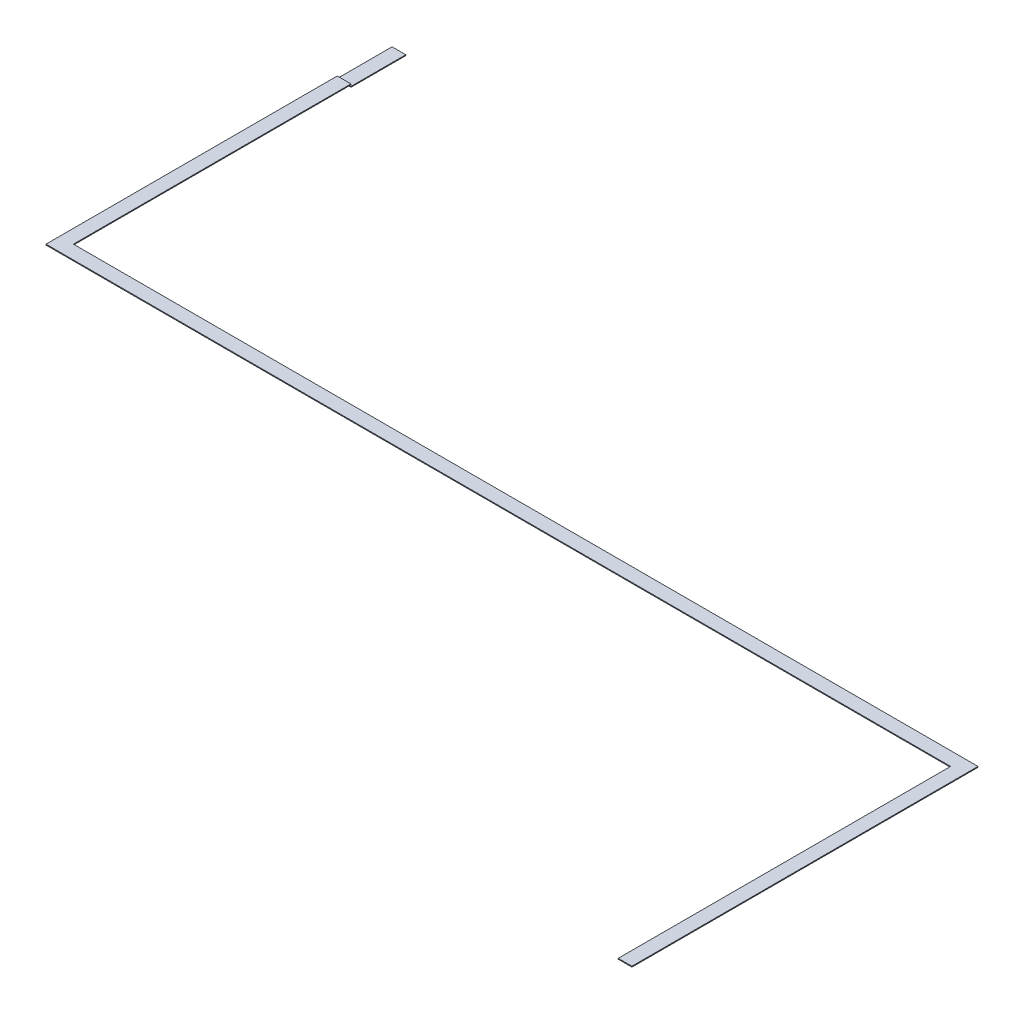
SolidWorks part; units mm, degrees
ref_plane "Front Plane" through (0, 0, 0) normal (0, 0, 1) x (1, 0, 0)
ref_plane "Top Plane" through (0, 0, 0) normal (0, 1, 0) x (1, 0, 0)
ref_plane "Right Plane" through (0, 0, 0) normal (1, 0, 0) x (0, 0, -1)
sketch "Sketch4" plane through (0, 0, 0) normal (0, 1, 0) x (1, 0, 0)
  line L1 (50.8, 0) -> (0, 0)
  line L2 (50.8, 0) -> (50.8, -1231.9)
  line L3 (50.8, -1231.9) -> (0, -1231.9)
  line L4 (0, 0) -> (0, -1231.9)
  line L5 (25.4, -1231.9) -> (25.4, 0) construction
  line L6 (50.8, -615.95) -> (0, -615.95) construction
  line L7 (0, -1231.9) -> (3403.6, -1231.9)
  line L8 (0, -1231.9) -> (0, -1282.7)
  line L9 (0, -1282.7) -> (3403.6, -1282.7)
  line L10 (3403.6, -1231.9) -> (3403.6, -1282.7)
  line L11 (1701.8, -1282.7) -> (1701.8, -1231.9) construction
  line L12 (0, -1257.3) -> (3403.6, -1257.3) construction
  line L13 (3403.6, -1231.9) -> (3352.8, -1231.9)
  line L14 (3403.6, -1231.9) -> (3403.6, -2514.6)
  line L15 (3403.6, -2514.6) -> (3352.8, -2514.6)
  line L16 (3352.8, -1231.9) -> (3352.8, -2514.6)
  line L17 (3378.2, -2514.6) -> (3378.2, -1231.9) construction
  line L18 (3403.6, -1873.25) -> (3352.8, -1873.25) construction
  point P150 (3378.2, -1873.25)
  point P232 (25.4, -615.95)
  point P309 (1701.8, -1257.3)
  dimension "D1" = 50.8
  dimension "D2" = 50.8
  dimension "D3" = 50.8
  dimension "D4" = 3352.8
  dimension "D5" = 1257.3
  dimension "D6" = 2514.6
extrude "Boss-Extrude4" add sketch "Sketch4" against normal blind 3.175
sketch "Sketch7" plane through (0, -3.175, 0) normal (0, -1, 0) x (1, 0, 0)
  line L0 (50.8, 0) -> (50.8, 1231.9) construction
  line L1 (0, 0) -> (50.8, 0)
  line L2 (0, 0) -> (0, 203.2)
  line L3 (0, 203.2) -> (50.8, 203.2)
  line L4 (50.8, 0) -> (50.8, 203.2)
  dimension "D1" = 203.2
extrude "Cut-Extrude1" cut sketch "Sketch7" against normal through all
ref_plane "Plane1" through (0, -7.9375, 0) normal (0, -1, 0) x (-1, 0, 0)
sketch "Sketch8" plane through (0, -7.9375, 0) normal (0, -1, 0) x (-1, 0, 0)
  line L1 (0, 0) -> (-50.8, 0)
  line L2 (0, 0) -> (0, -203.2)
  line L3 (0, -203.2) -> (-50.8, -203.2)
  line L4 (-50.8, 0) -> (-50.8, -203.2)
extrude "Boss-Extrude5" add sketch "Sketch8" along normal blind 3.175 separate body
ref_plane "Plane2" [suppressed] through (0, 4.7625, 0) normal (0, 1, 0) x (1, 0, 0)
sketch "Sketch9" [suppressed] plane through (0, 4.7625, 0) normal (0, 1, 0) x (1, 0, 0)
  line L1 (0, 0) -> (50.8, 0)
  line L2 (0, 0) -> (0, -203.2)
  line L3 (0, -203.2) -> (50.8, -203.2)
  line L4 (50.8, 0) -> (50.8, -203.2)
extrude "Boss-Extrude6" [suppressed] add sketch "Sketch9" along normal blind 3.175 separate body
